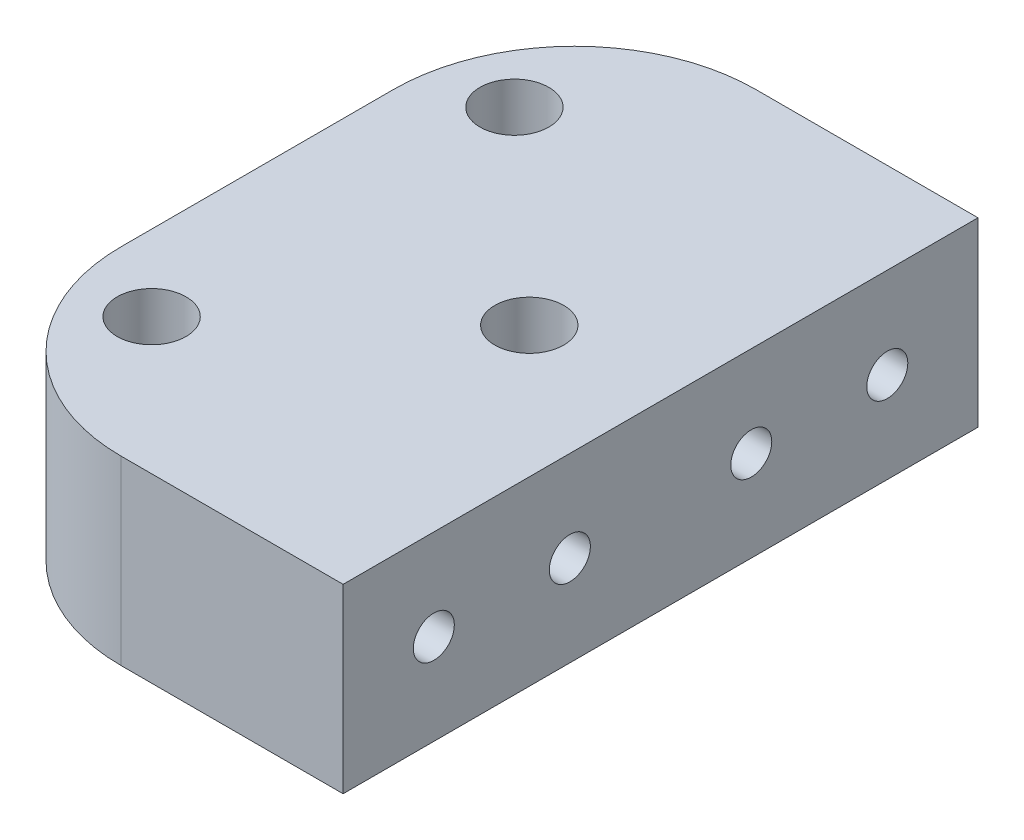
SolidWorks part; units mm, degrees
ref_plane "Front Plane" through (0, 0, 0) normal (0, 0, 1) x (1, 0, 0)
ref_plane "Top Plane" through (0, 0, 0) normal (0, 1, 0) x (1, 0, 0)
ref_plane "Right Plane" through (0, 0, 0) normal (1, 0, 0) x (0, 0, -1)
sketch "Sketch1" plane through (0, 0, 0) normal (0, 1, 0) x (1, 0, 0)
  line L1 (-11.1188, 17.5) -> (11.1187, 17.5)
  line L2 (-11.1188, 17.5) -> (-11.1187, -17.5)
  line L3 (-11.1187, -17.5) -> (11.1188, -17.5)
  line L4 (11.1187, 17.5) -> (11.1188, -17.5)
  line L5 (-11.1188, 17.5) -> (11.1188, -17.5) construction
  line L6 (-11.1187, -17.5) -> (11.1187, 17.5) construction
  point P0 (0, 0)
  dimension "D1" = 35
  dimension "D2" = 22.2375
extrude "Boss-Extrude1" add sketch "Sketch1" along normal blind 10
hole_wizard "#4-40 Tapped Hole1" positions "Sketch2" profile "Sketch3" tap size "#4-40" standard "ANSI Inch"
sketch "Sketch2" plane through (11.1188, 0, 0) normal (1, 0, 0) x (0, 0, -1)
  line L0 (-17.5, 0) -> (17.5, 0) construction
  line L1 (-17.5, 10) -> (-17.5, 0) construction
  line L2 (17.5, 10) -> (17.5, 0) construction
  point P0 (-12.5, 5)
  point P4 (12.5, 5)
  point P18 (-5, 5)
  point P20 (5, 5)
  dimension "D1" = 5
  dimension "D2" = 5
  dimension "D3" = 5
  dimension "D4" = 7.5
  dimension "D5" = 7.5
cosmetic thread "Hole Thread1"
cosmetic thread "Hole Thread2"
cosmetic thread "Hole Thread3"
sketch "Sketch3" plane through (11.1188, 5, 12.5) normal (0, 1, 0) x (0, 0, -1)
  line L0 (0, 0) -> (0, 8.2792)
  line L1 (0, 8.2792) -> (1.1303, 7.6)
  line L2 (1.1303, 7.6) -> (1.1303, 0)
  line L5 (1.1303, 0) -> (0, 0)
  line L10 (0, 8.2792) -> (-1.1303, 7.6) construction
  line L11 (0, -6.35) -> (0, 107.95) construction
  dimension "Tap Drill Dia." = 2.2606
  dimension "Tap Drill Depth" = 7.6
  dimension "Drill Angle" = 118
cosmetic thread "Hole Thread4"
hole_wizard "#6 Clearance Hole1" positions "Sketch4" profile "Sketch5" hole size "#6" standard "ANSI Inch" end condition through all
sketch "Sketch4" plane through (0, 10, 0) normal (0, 1, 0) x (1, 0, 0)
  line L0 (-11.1188, 17.5) -> (-11.1187, -17.5) construction
  point P0 (3.8812, 0)
  point P2 (-6.9388, 10)
  point P4 (-6.9388, -10)
  dimension "D1" = 10.82
  dimension "D2" = 10
  dimension "D3" = 10
  dimension "D4" = 15
sketch "Sketch5" plane through (3.8812, 10, 0) normal (1, 0, 0) x (0, 0, 1)
  line L0 (0, 0) -> (0, 10)
  line L1 (0, 10) -> (1.8986, 10)
  line L2 (1.8986, 10) -> (1.8986, 0)
  line L5 (1.8986, 0) -> (0, 0)
  line L11 (0, -6.35) -> (0, 107.95) construction
  dimension "Thru Hole Dia." = 3.7973
  dimension "Thru Hole Depth" = 10
fillet "Fillet1" radius 10 2 edges at (-11.1187, 5, 17.5) (-11.1188, 5, -17.5)
equation "\"D3@Sketch2\"=\"D2@Sketch2\""
equation "\"D3@Sketch4\"=\"D2@Sketch4\""
equation "\"D5@Sketch2\"=\"D4@Sketch2\""
